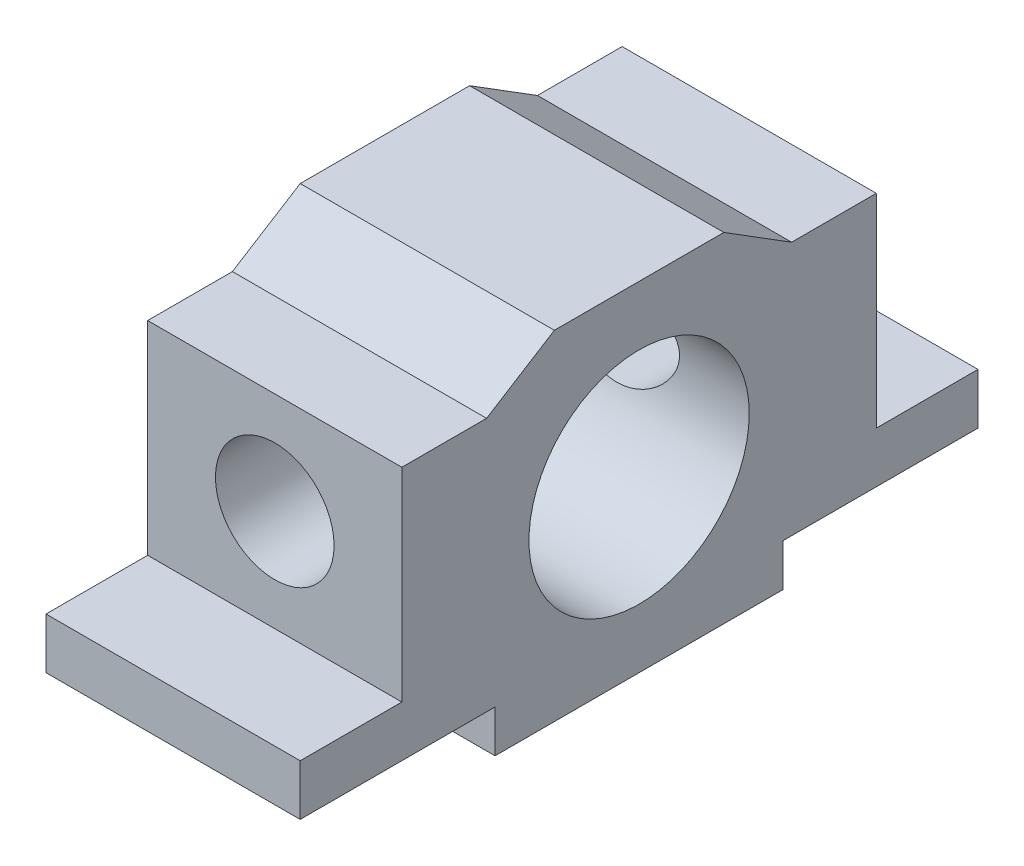
SolidWorks part; units mm, degrees
ref_plane "Front Plane" through (0, 0, 0) normal (0, 0, 1) x (1, 0, 0)
ref_plane "Top Plane" through (0, 0, 0) normal (0, 1, 0) x (1, 0, 0)
ref_plane "Right Plane" through (0, 0, 0) normal (1, 0, 0) x (0, 0, -1)
sketch "Sketch1" plane through (0, 0, 0) normal (0, 0, 1) x (1, 0, 0)
  line L1 (0, 0) -> (30, 0)
  line L2 (0, 0) -> (0, 40)
  line L3 (0, 40) -> (30, 40)
  line L4 (30, 0) -> (30, 40)
  dimension "D1" = 30
  dimension "D2" = 40
extrude "Boss-Extrude1" add sketch "Sketch1" along normal mid plane 80
sketch "Sketch2" plane through (0, 0, 40) normal (0, 0, 1) x (1, 0, 0)
  line L0 (0, 5) -> (30, 5)
  line L1 (0, 40) -> (0, 0) construction
  line L2 (30, 0) -> (30, 40) construction
  line L3 (30, 5) -> (30, 0)
  line L4 (30, 0) -> (0, 0)
  line L5 (0, 0) -> (0, 5)
  dimension "D1" = 5
extrude "Cut-Extrude1" cut sketch "Sketch2" against normal blind 23
sketch "Sketch3" plane through (0, 0, -40) normal (0, 0, -1) x (-1, 0, 0)
  line L0 (-30, 5) -> (0, 5)
  line L1 (0, 40) -> (0, 0) construction
  line L2 (0, 5) -> (0, 0)
  line L3 (0, 0) -> (-30, 0)
  line L4 (-30, 0) -> (-30, 5)
extrude "Cut-Extrude2" cut sketch "Sketch3" against normal blind 23
sketch "Sketch5" plane through (0, 0, 0) normal (1, 0, 0) x (0, 0, -1)
  line L0 (-28, 40) -> (-28, 11)
  line L1 (-40, 40) -> (40, 40) construction
  line L2 (-28, 11) -> (-40, 11)
  line L3 (-40, 5) -> (-40, 40) construction
  line L4 (-40, 11) -> (-40, 40)
  line L5 (-40, 40) -> (-28, 40)
  line L6 (28, 40) -> (40, 40)
  line L7 (40, 40) -> (40, 11)
  line L11 (28, 11) -> (28, 40)
  line L12 (28, 11) -> (40, 11)
  point P12 (0, 0)
  dimension "D1" = 12
  dimension "D2" = 12
  dimension "D3" = 6
extrude "Cut-Extrude3" cut sketch "Sketch5" along normal through all
sketch "Sketch6" plane through (30, 0, 0) normal (1, 0, 0) x (0, 0, -1)
  line L0 (-28, 35) -> (-18, 35)
  line L1 (-28, 11) -> (-28, 40) construction
  line L2 (-18, 35) -> (-10, 40)
  line L3 (-28, 40) -> (28, 40) construction
  line L5 (10, 40) -> (18, 35)
  line L6 (18, 35) -> (28, 35)
  line L7 (28, 40) -> (28, 11) construction
  line L8 (28, 35) -> (28, 40)
  line L9 (28, 40) -> (10, 40)
  line L10 (-28, 40) -> (-10, 40)
  line L11 (-28, 40) -> (-28, 35)
  point P15 (0, 0)
  point P20 (0, 0)
  dimension "D1" = 35
  dimension "D2" = 36
  dimension "D3" = 20
  dimension "D4" = 18
extrude "Cut-Extrude4" cut sketch "Sketch6" against normal through all
sketch "Sketch7" plane through (30, 0, 0) normal (1, 0, 0) x (0, 0, -1)
  line L0 (-10, 40) -> (10, 40) construction
  circle A0 centre (0, 20) radius 13
  point P7 (0, 0)
  point P8 (0, 0)
  point P9 (0, 20)
  dimension "D1" = 26
  dimension "D2" = 20
extrude "Cut-Extrude5" cut sketch "Sketch7" against normal through all
sketch "Sketch8" plane through (0, 0, 28) normal (0, 0, 1) x (1, 0, 0)
  line L0 (30, 11) -> (0, 11) construction
  line L6 (0, 11) -> (0, 35) construction
  circle A0 centre (15, 23) radius 7
  point P2 (0, 0)
  point P4 (0, 22.2592)
  dimension "D1" = 14
  dimension "D2" = 12
  dimension "D3" = 15
extrude "Cut-Extrude6" cut sketch "Sketch8" against normal through all
